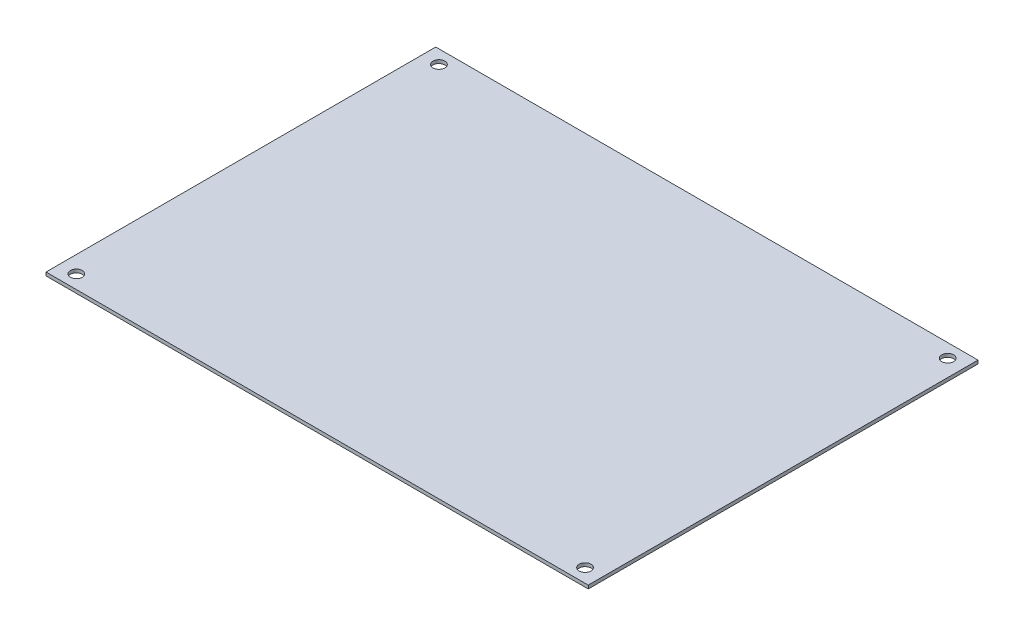
SolidWorks part; units mm, degrees
ref_plane "Front Plane" through (0, 0, 0) normal (0, 0, 1) x (1, 0, 0)
ref_plane "Top Plane" through (0, 0, 0) normal (0, 1, 0) x (1, 0, 0)
ref_plane "Right Plane" through (0, 0, 0) normal (1, 0, 0) x (0, 0, -1)
sketch "Sketch1" plane through (0, 0, 0) normal (0, 1, 0) x (1, 0, 0)
  line L1 (-66.9001, 58.0256) -> (93.0999, 58.0256)
  line L2 (-66.9001, 58.0256) -> (-66.9001, -56.9744)
  line L3 (-66.9001, -56.9744) -> (93.0999, -56.9744)
  line L4 (93.0999, 58.0256) -> (93.0999, -56.9744)
  dimension "D1" = 160
  dimension "D2" = 115
extrude "Boss-Extrude1" add sketch "Sketch1" along normal blind 1
sketch "Sketch2" plane through (0, 1, 0) normal (0, 1, 0) x (1, 0, 0)
  line L0 (-66.9001, -56.9744) -> (93.0999, -56.9744) construction
  line L1 (-66.9001, 58.0256) -> (-66.9001, -56.9744) construction
  line L2 (93.0999, 58.0256) -> (-66.9001, 58.0256) construction
  line L3 (93.0999, -56.9744) -> (93.0999, 58.0256) construction
  circle A0 centre (-61.9551, -52.9744) radius 1.75
  circle A1 centre (-61.9551, 54.0256) radius 1.75
  circle A2 centre (88.1549, -52.9744) radius 1.75
  circle A3 centre (88.1549, 54.0256) radius 1.75
  dimension "D1" = 3.5
  dimension "D2" = 4
  dimension "D3" = 4.945
  dimension "D4" = 4.945
  dimension "D5" = 4
  dimension "D6" = 4
  dimension "D7" = 4.945
  dimension "D8" = 4.945
  dimension "D9" = 4
extrude "Cut-Extrude1" cut sketch "Sketch2" against normal through all
